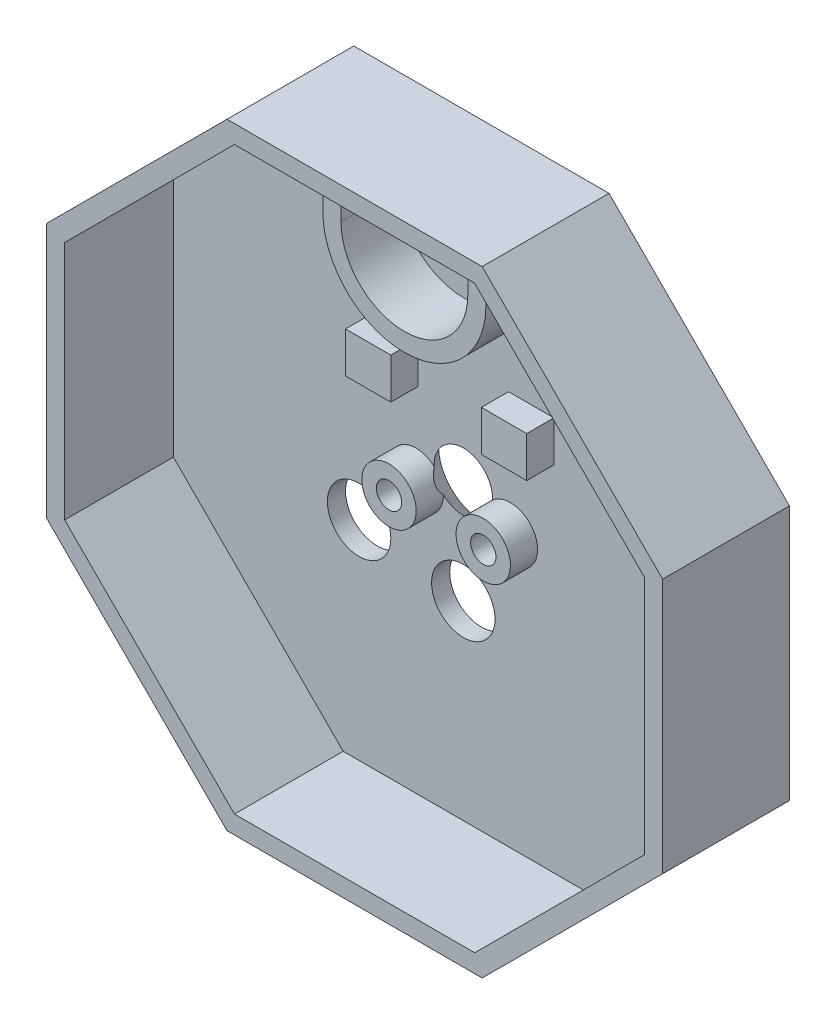
SolidWorks part; units mm, degrees
ref_plane "Front Plane" through (0, 0, 0) normal (0, 0, 1) x (1, 0, 0)
ref_plane "Top Plane" through (0, 0, 0) normal (0, 1, 0) x (1, 0, 0)
ref_plane "Right Plane" through (0, 0, 0) normal (1, 0, 0) x (0, 0, -1)
sketch "Sketch1" plane through (0, 0, 0) normal (0, 0, 1) x (1, 0, 0)
  line L1 (34, -14.0833) -> (34, 14.0833)
  line L2 (34, 14.0833) -> (14.0833, 34)
  line L3 (14.0833, 34) -> (-14.0833, 34)
  line L4 (-14.0833, 34) -> (-34, 14.0833)
  line L5 (-34, 14.0833) -> (-34, -14.0833)
  line L6 (-34, -14.0833) -> (-14.0833, -34)
  line L7 (-14.0833, -34) -> (14.0833, -34)
  line L8 (14.0833, -34) -> (34, -14.0833)
  circle A0 centre (0, 0) radius 34 construction
  point P1 (36.8254, -11.9683)
  point P12 (31.5, -13.0477)
  dimension "D1" = 68
extrude "Boss-Extrude1" add sketch "Sketch1" along normal blind 14
shell "Shell1" thickness 2
sketch "Sketch2" plane through (0, 0, 2) normal (0, 0, 1) x (1, 0, 0)
  line L0 (-7, 32) -> (7, 32) construction
  line L2 (7, 32) -> (7, 25)
  line L3 (-7, 32) -> (-7, 25)
  line L4 (0, 32) -> (0, 25) construction
  line L5 (13.2548, 32) -> (-13.2548, 32) construction
  line L6 (-9, 32) -> (-9, 25)
  line L7 (9, 32) -> (9, 25)
  line L8 (-9, 32) -> (-7, 32)
  line L9 (7, 32) -> (9, 32)
  circle A0 centre (0, 25) radius 5 construction
  arc A1 (7, 25) -> (-7, 25) centre (0, 25) cw
  arc A2 (9, 25) -> (-9, 25) centre (0, 25) cw
  dimension "D1" = 2
  dimension "D2" = 2
extrude "Boss-Extrude2" add sketch "Sketch2" along normal up to surface (6.5 mm away)
sketch "Sketch3" plane through (0, 0, 2) normal (0, 0, 1) x (1, 0, 0)
  circle A0 centre (0, 25) radius 4.19
  circle A1 centre (0, 25) radius 5 construction
  dimension "D1" = 0.81
extrude "Cut-Extrude1" cut sketch "Sketch3" against normal through all
sketch "Sketch8" plane through (0, 0, 2) normal (0, 0, 1) x (1, 0, 0)
  circle A0 centre (-5.2, -2) radius 3
  circle A1 centre (-5.2, -2) radius 1.4
  circle A2 centre (-5.2, -2) radius 1.8 construction
  point P3 (0, 0)
  dimension "D1" = 2.8
  dimension "D2" = 1.6
extrude "Boss-Extrude3" add sketch "Sketch8" along normal up to surface (3 mm away)
mirror "Mirror1" about plane through (0, 0, 0) normal (1, 0, 0) of "Boss-Extrude3"
sketch "Sketch6" plane through (0, 0, 0) normal (1, 0, 0) x (0, 0, -1)
  line L0 (-6.3, 0.4) -> (0, 0.4)
  line L1 (0, -14.0833) -> (0, 14.0833) construction
  line L2 (0, 0.4) -> (0, -4.325)
  line L3 (0, -4.325) -> (-6.3, 0.4)
  line L4 (-3.5, -1.7) -> (-3.5, 2.5) construction
  point P4 (-3.5, 0.4)
  point P6 (0, 0)
  point P9 (-10.2014, 8.1)
  point P11 (-6.3296, 8.1)
  dimension "D1" = 6.3
revolve "Cut-Revolve1" cut sketch "Sketch6" angle 360 about L0
sketch "Sketch9" plane through (0, 0, 2) normal (0, 0, 1) x (1, 0, 0)
  line L1 (-10, 7) -> (-5, 7)
  line L2 (-10, 7) -> (-10, 11.5)
  line L3 (-10, 11.5) -> (-5, 11.5)
  line L4 (-4, 7) -> (-4, 11.5) construction
  line L5 (-10, 7) -> (-5, 11.5) construction
  line L6 (-10, 11.5) -> (-5, 7) construction
  line L9 (0, 0) -> (0, -4.6859) construction
  line L10 (-4, 11.5) -> (4, 11.5) construction
  line L11 (-5, 7) -> (-5, 11.5)
  line L12 (4, 7) -> (-4, 7) construction
  line L13 (0, 11.5) -> (0, 7) construction
  line L14 (10, 7) -> (10, 11.5)
  line L15 (10, 7) -> (5, 7)
  line L16 (5, 7) -> (5, 11.5)
  line L17 (10, 11.5) -> (5, 11.5)
  point P0 (-7.5, 9.25)
  dimension "D1" = 1
  dimension "D2" = 5
extrude "Boss-Extrude4" add sketch "Sketch9" along normal up to surface (3 mm away) up to face at (-5.2, -0.6, 5)
sketch "Sketch10" plane through (0, 0, 0) normal (0, 0, -1) x (-1, 0, 0)
  circle A0 centre (11.5, -9) radius 3.5
  circle A1 centre (11.5, -9) radius 3 construction
  circle A2 centre (0, -11) radius 3.5
  circle A3 centre (0, -11) radius 3 construction
  dimension "D1" = 7
  dimension "D2" = 7
extrude "Cut-Extrude2" cut sketch "Sketch10" against normal through all
